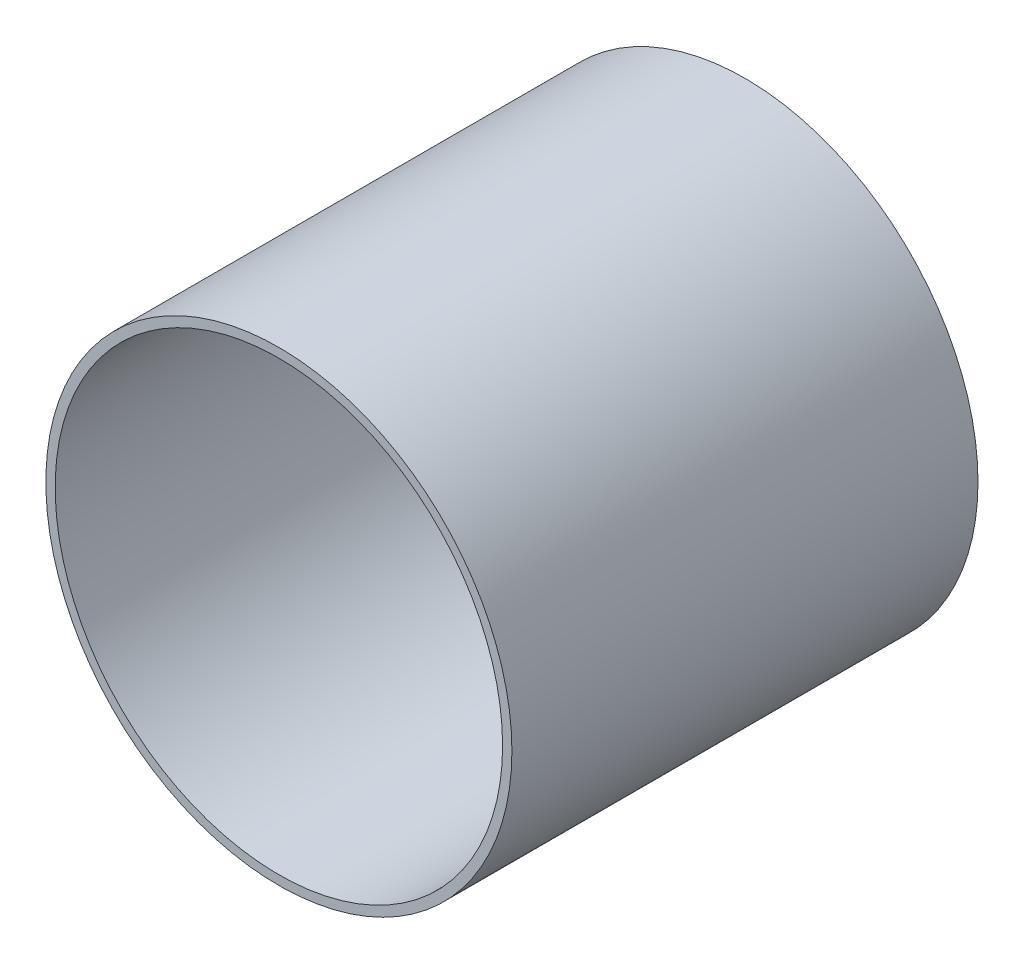
SolidWorks part; units mm, degrees
ref_plane "Front Plane" through (0, 0, 0) normal (0, 0, 1) x (1, 0, 0)
ref_plane "Top Plane" through (0, 0, 0) normal (0, 1, 0) x (1, 0, 0)
ref_plane "Right Plane" through (0, 0, 0) normal (1, 0, 0) x (0, 0, -1)
sketch "Sketch1" plane through (0, 0, 0) normal (0, 0, 1) x (1, 0, 0)
  circle A0 centre (0, 0) radius 50
  circle A1 centre (0, 0) radius 48
  dimension "D1" = 100
  dimension "D2" = 2
extrude "Boss-Extrude1" add sketch "Sketch1" along normal blind 100
